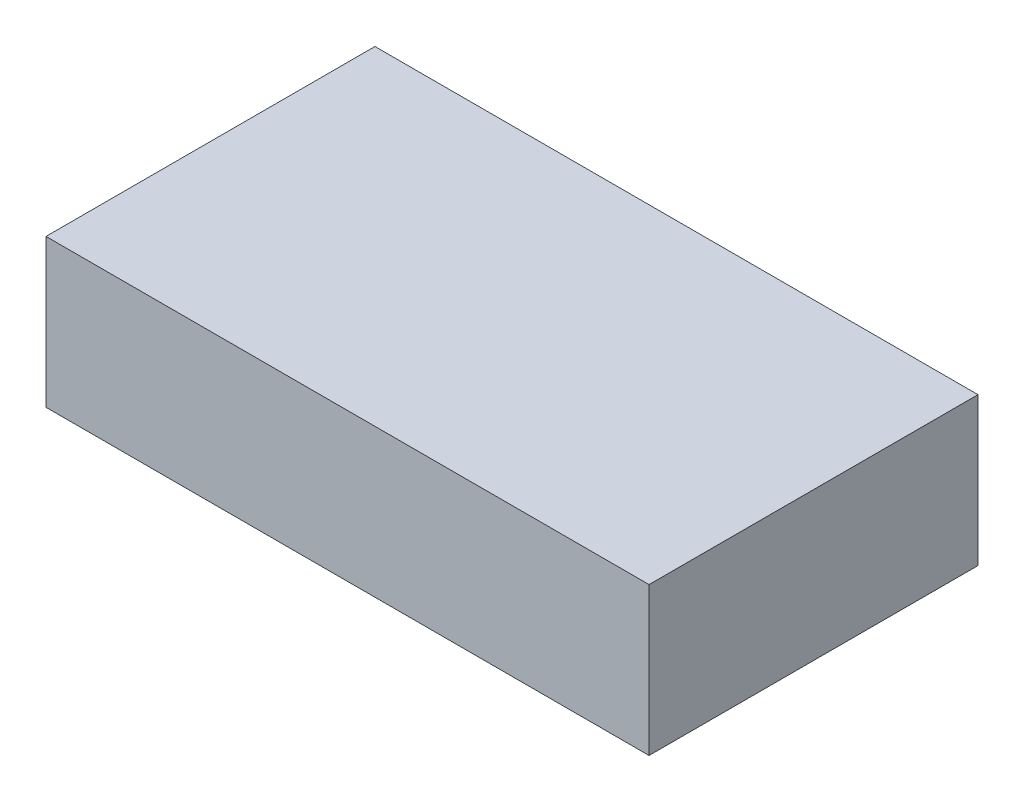
SolidWorks part; units mm, degrees
ref_plane "Front Plane" through (0, 0, 0) normal (0, 0, 1) x (1, 0, 0)
ref_plane "Top Plane" through (0, 0, 0) normal (0, 1, 0) x (1, 0, 0)
ref_plane "Right Plane" through (0, 0, 0) normal (1, 0, 0) x (0, 0, -1)
sketch "Sketch1" plane through (0, 0, 0) normal (0, 1, 0) x (1, 0, 0)
  line L1 (0, 0) -> (220, 0)
  line L2 (0, 0) -> (0, 120)
  line L3 (0, 120) -> (220, 120)
  line L4 (220, 0) -> (220, 120)
  dimension "D1" = 220
  dimension "D2" = 120
extrude "Boss-Extrude1" add sketch "Sketch1" along normal blind 54
